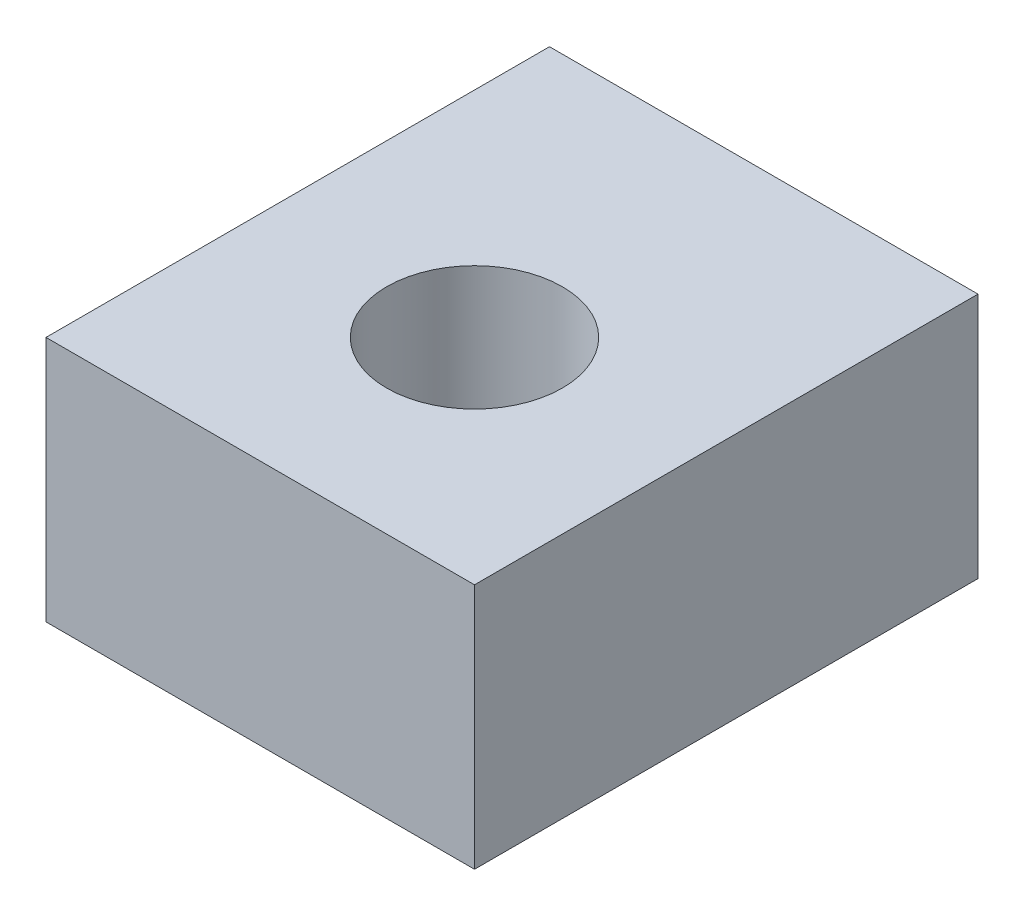
SolidWorks part; units mm, degrees
ref_plane "Front Plane" through (0, 0, 0) normal (0, 0, 1) x (1, 0, 0)
ref_plane "Top Plane" through (0, 0, 0) normal (0, 1, 0) x (1, 0, 0)
ref_plane "Right Plane" through (0, 0, 0) normal (1, 0, 0) x (0, 0, -1)
sketch "Sketch1" plane through (0, 0, 0) normal (0, 1, 0) x (1, 0, 0)
  line L1 (-10, -11.75) -> (10, -11.75)
  line L2 (-10, -11.75) -> (-10, 11.75)
  line L3 (-10, 11.75) -> (10, 11.75)
  line L4 (10, -11.75) -> (10, 11.75)
  line L5 (-10, -11.75) -> (10, 11.75) construction
  line L6 (-10, 11.75) -> (10, -11.75) construction
  circle A0 centre (0, -1.75) radius 4.1
  point P0 (0, 0)
  dimension "D3" = 8.2
  dimension "D1" = 23.5
  dimension "D2" = 20
  dimension "D4" = 10
extrude "Boss-Extrude1" add sketch "Sketch1" along normal blind 11.5
